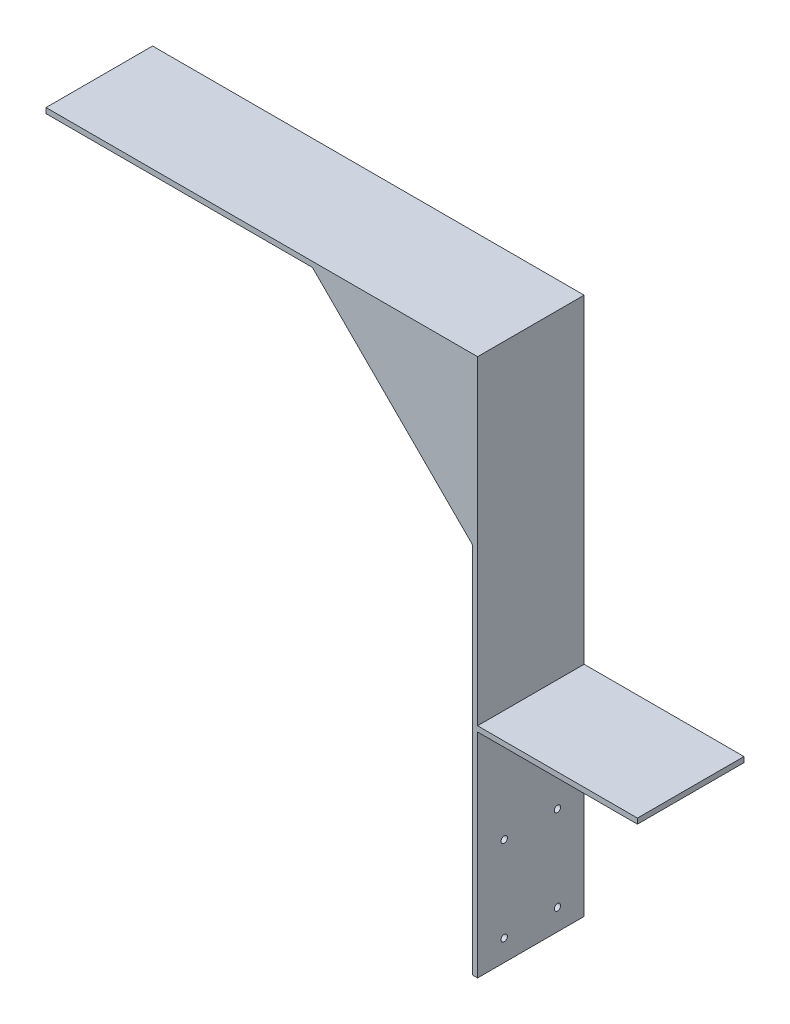
SolidWorks part; units mm, degrees
ref_plane "Front Plane" through (0, 0, 0) normal (0, 0, 1) x (1, 0, 0)
ref_plane "Top Plane" through (0, 0, 0) normal (0, 1, 0) x (1, 0, 0)
ref_plane "Right Plane" through (0, 0, 0) normal (1, 0, 0) x (0, 0, -1)
sketch "Sketch1" plane through (0, 0, 0) normal (0, 0, 1) x (1, 0, 0)
  line L0 (0, 0) -> (0, 500)
  line L1 (0, 500) -> (-400, 500)
  dimension "D1" = 500
  dimension "D2" = 90
  dimension "D4" = 400
extrude "Extrude-Thin1" add sketch "Sketch1" along normal blind 100 thin
hole_wizard "Ø6.0mm Dowel Hole1" positions "Sketch6" profile "Sketch7" hole size "Ø6.0" standard "BSI" end condition through all
sketch "Sketch6" plane through (5, 0, 0) normal (1, 0, 0) x (0, 0, -1)
  line L3 (-100, 0) -> (0, 0) construction
  line L4 (-100, 0) -> (-100, 505) construction
  point P0 (-25, 100)
  point P2 (-75, 100)
  point P4 (-75, 20)
  point P6 (-25, 20)
  dimension "D1" = 50
  dimension "D2" = 50
  dimension "D3" = 100
  dimension "D4" = 20
  dimension "D5" = 25
  dimension "D6" = 25
sketch "Sketch7" plane through (5, 100, 25) normal (0, 1, 0) x (0, 0, -1)
  line L0 (0, 0) -> (0, 405)
  line L1 (0, 405) -> (3, 405)
  line L2 (3, 405) -> (3, 0)
  line L5 (3, 0) -> (0, 0)
  line L11 (0, -6.35) -> (0, 107.95) construction
  dimension "Thru Hole Dia." = 6
  dimension "Thru Hole Depth" = 405
sketch "Sketch8" plane through (5, 0, 0) normal (1, 0, 0) x (0, 0, -1)
  line L0 (-100, 0) -> (-100, 505) construction
  line L1 (-100, 205) -> (0, 205)
  line L2 (-100, 205) -> (-100, 200)
  line L3 (-100, 200) -> (0, 200)
  line L4 (0, 205) -> (0, 200)
  line L5 (0, 0) -> (0, 505) construction
  line L7 (-100, 0) -> (0, 0) construction
  dimension "D1" = 5
  dimension "D2" = 200
extrude "Boss-Extrude3" add sketch "Sketch8" along normal blind 150
sketch "Sketch9" plane through (0, 0, 100) normal (0, 0, 1) x (1, 0, 0)
  line L0 (-150, 500) -> (0, 350)
  line L1 (0, 500) -> (-400, 500) construction
  line L2 (0, 0) -> (0, 500) construction
  line L3 (0, 350) -> (0, 500)
  line L4 (0, 500) -> (-150, 500)
  dimension "D1" = 150
  dimension "D2" = 150
extrude "Boss-Extrude4" add sketch "Sketch9" against normal blind 5
